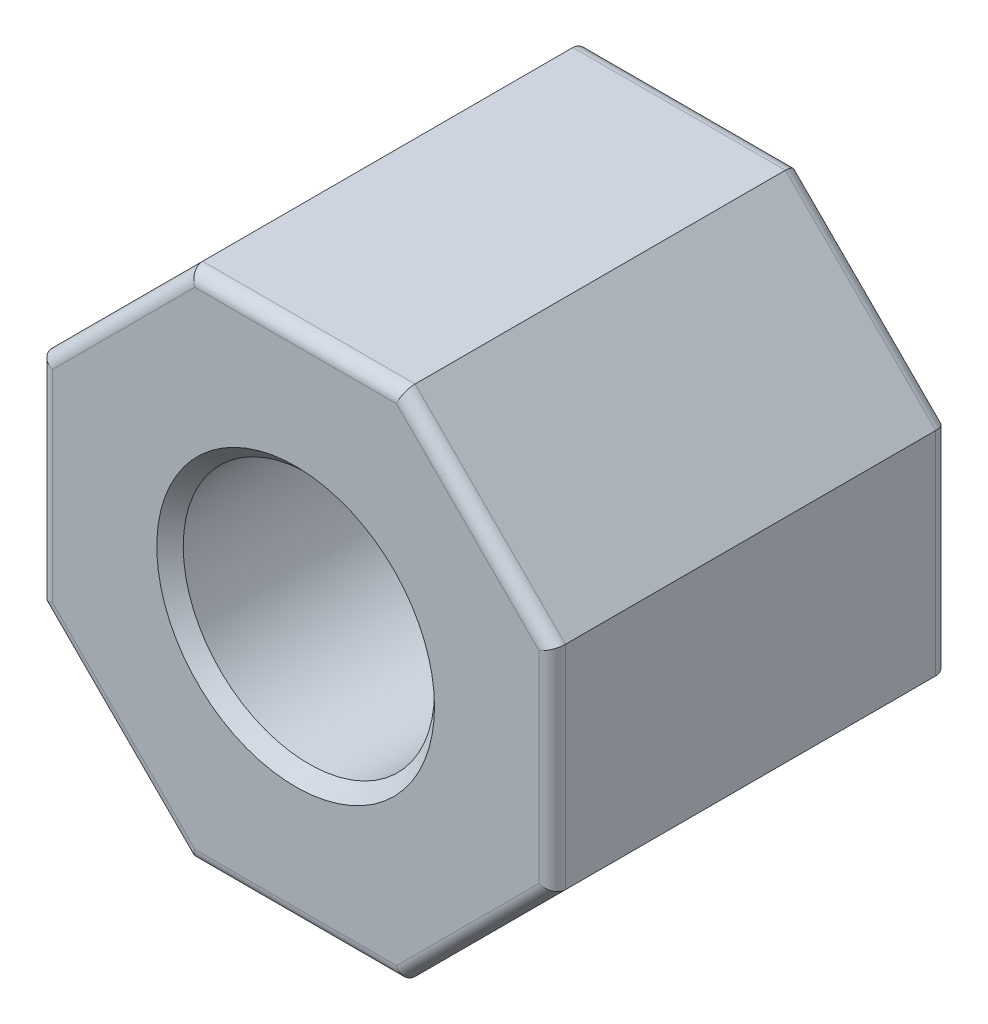
SolidWorks part; units mm, degrees
ref_plane "Piano frontale" through (0, 0, 0) normal (0, 0, 1) x (1, 0, 0)
ref_plane "Piano superiore" through (0, 0, 0) normal (0, 1, 0) x (1, 0, 0)
ref_plane "Piano destro" through (0, 0, 0) normal (1, 0, 0) x (0, 0, -1)
sketch "Schizzo1" plane through (0, 0, 0) normal (0, 0, 1) x (1, 0, 0)
  line L0 (0, 21) -> (0, -21) construction
  line L1 (-21, 0) -> (21, 0) construction
  line L2 (-19.4015, 8.0364) -> (-19.4015, -8.0364)
  line L3 (-19.4015, -8.0364) -> (-8.0364, -19.4015)
  line L4 (-8.0364, -19.4015) -> (8.0364, -19.4015)
  line L5 (8.0364, -19.4015) -> (19.4015, -8.0364)
  line L6 (19.4015, -8.0364) -> (19.4015, 8.0364)
  line L7 (19.4015, 8.0364) -> (8.0364, 19.4015)
  line L8 (8.0364, 19.4015) -> (-8.0364, 19.4015)
  line L9 (-8.0364, 19.4015) -> (-19.4015, 8.0364)
  circle A0 centre (0, 0) radius 21
  dimension "D1" = 42
extrude "Estrusione-Estrusione1" add sketch "Schizzo1" along normal blind 30 contours L8 L9 L2 L3 L4 L5 L6 L7
sketch "Schizzo2" plane through (0, 0, 0) normal (0, 0, -1) x (-1, 0, 0)
  circle A0 centre (0, 0) radius 9.5
  dimension "D1" = 19
extrude "Taglio-Estrusione1" cut sketch "Schizzo2" against normal through all
chamfer "Smusso1" distance 1 angle 45 2 edges at (-9.5, 0, 30) (-9.5, 0, 0)
fillet "Raccordo1" radius 1 16 edges at (19.4015, 0, 0) (13.7189, -13.7189, 0) (0, -19.4015, 0) (-13.7189, -13.7189, 0) (-19.4015, 0, 0) (0, 19.4015, 0) (-13.7189, 13.7189, 0) (13.7189, 13.7189, 0) (0, -19.4015, 30) (-13.7189, -13.7189, 30) (-19.4015, 0, 30) (13.7189, -13.7189, 30) (19.4015, 0, 30) (13.7189, 13.7189, 30) (0, 19.4015, 30) (-13.7189, 13.7189, 30)
